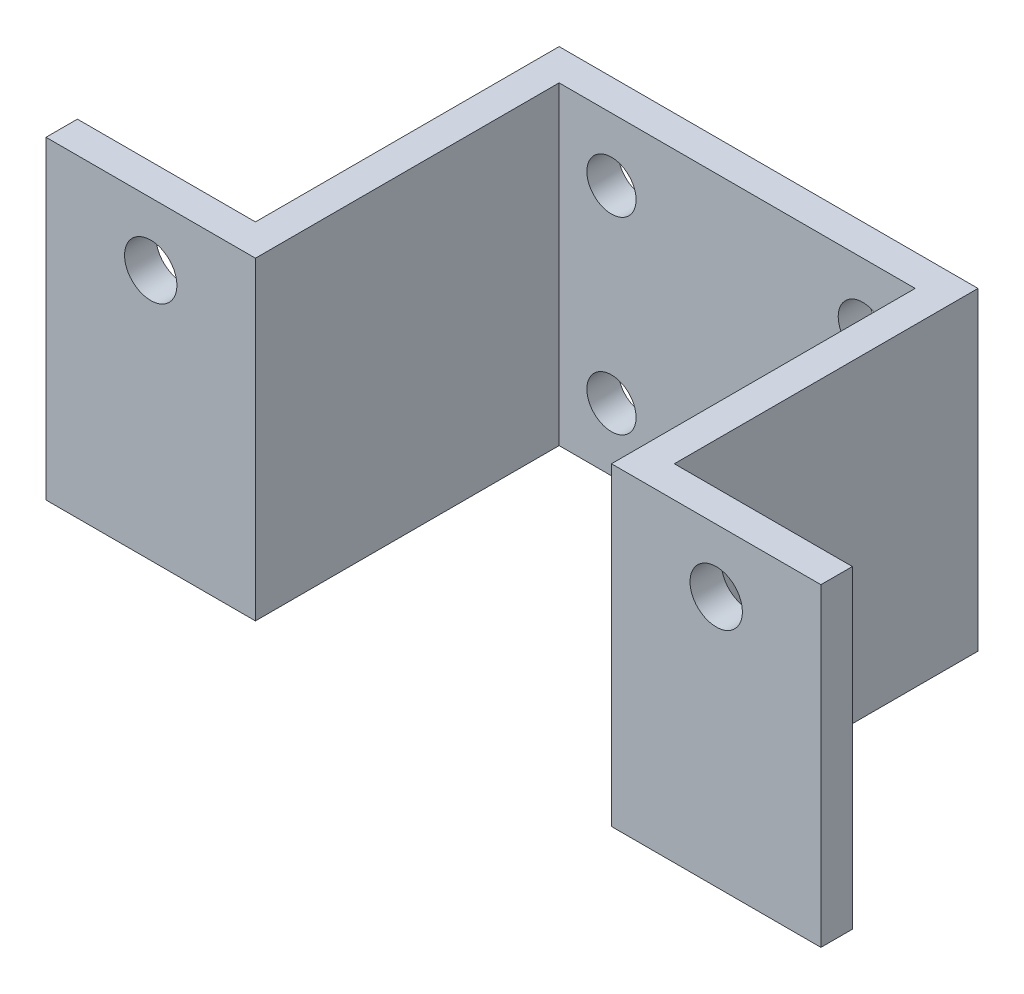
SolidWorks part; units mm, degrees
ref_plane "Front Plane" through (0, 0, 0) normal (0, 0, 1) x (1, 0, 0)
ref_plane "Top Plane" through (0, 0, 0) normal (0, 1, 0) x (1, 0, 0)
ref_plane "Right Plane" through (0, 0, 0) normal (1, 0, 0) x (0, 0, -1)
sketch "Sketch1" plane through (0, 0, 0) normal (0, 1, 0) x (1, 0, 0)
  line L0 (0, 0) -> (0, 29)
  line L1 (0, 0) -> (17, 0)
  line L2 (0, 0) -> (-17, 0)
  line L3 (-20, 0) -> (-20, 32)
  line L4 (-17, 0) -> (17, 0)
  line L5 (-17, 0) -> (-17, 29)
  line L6 (-17, 29) -> (17, 29)
  line L7 (17, 0) -> (17, 29)
  line L8 (-20, 32) -> (20, 32)
  line L9 (20, 0) -> (20, 32)
  line L10 (-37, 0) -> (-37, 3)
  line L11 (17, 0) -> (37, 0)
  line L12 (17, 0) -> (17, 3)
  line L13 (17, 3) -> (37, 3)
  line L14 (37, 0) -> (37, 3)
  line L15 (-17, 3) -> (-37, 3)
  line L16 (-17, 0) -> (-37, 0)
  dimension "D1" = 3
extrude "Boss-Extrude1" add sketch "Sketch1" along normal blind 30 contours L15 L5 L6 L7 L13 L9 L8 L3 | L16 L5 L15 L3 | L16 L3 L15 L10 | L13 L7 L11 L9 | L11 L14 L13 L9
sketch "Sketch2" plane through (0, 0, 0) normal (0, 0, 1) x (1, 0, 0)
  line L0 (-27, 30) -> (-27, 24)
  line L3 (-17, 30) -> (-37, 30) construction
  line L4 (-17, 30) -> (17, 30) construction
  line L5 (0, 30) -> (0, 0)
  circle A0 centre (-27, 24) radius 2.5
  circle A1 centre (27, 24) radius 2.5
  point P4 (-27, 23.4386)
extrude "Cut-Extrude1" cut sketch "Sketch2" against normal blind 30 contours A0 | A1
sketch "Sketch3" plane through (0, 0, -32) normal (0, 0, -1) x (-1, 0, 0)
  circle A0 centre (-12, 6) radius 2.35
  circle A1 centre (12, 6) radius 2.35
  circle A2 centre (12, 24) radius 2.35
  circle A3 centre (-12, 24) radius 2.35
extrude "Cut-Extrude2" cut sketch "Sketch3" against normal blind 30
